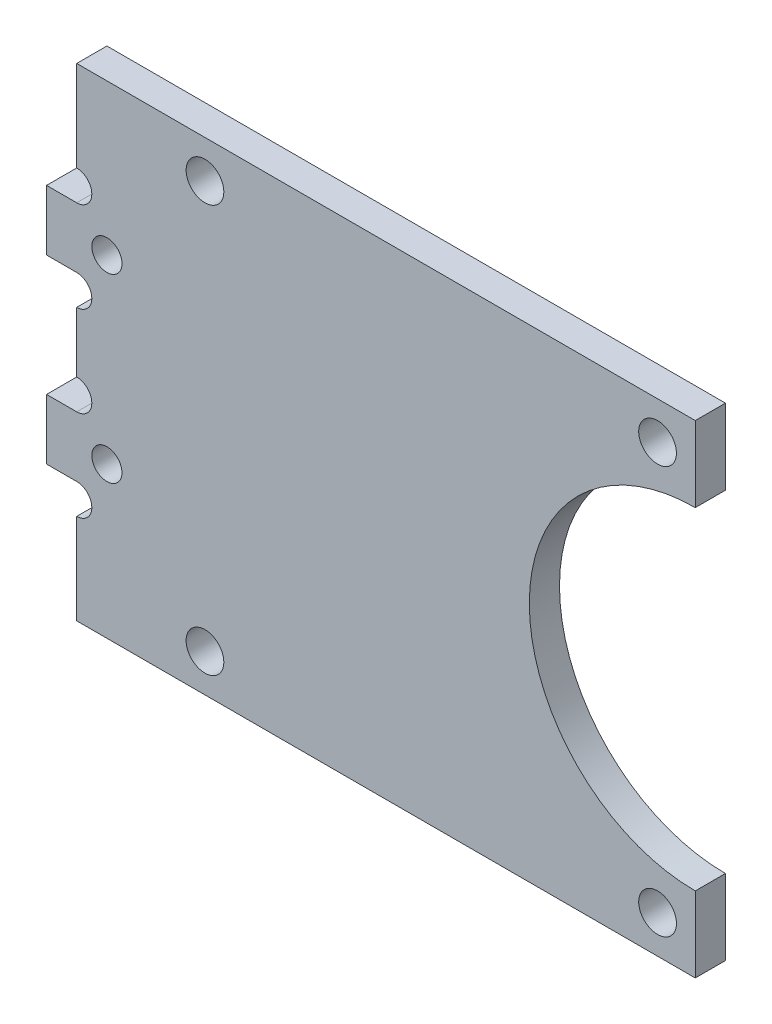
SolidWorks part; units mm, degrees
material "自訂玻璃纖維"
ref_plane "前基準面" through (0, 0, 0) normal (0, 0, 1) x (1, 0, 0)
ref_plane "上基準面" through (0, 0, 0) normal (0, 1, 0) x (1, 0, 0)
ref_plane "右基準面" through (0, 0, 0) normal (1, 0, 0) x (0, 0, -1)
sketch "草圖1" plane through (0, 0, 0) normal (0, 0, 1) x (1, 0, 0)
  line L0 (-17.2162, 10.1625) -> (15.2838, 10.1625)
  line L1 (15.2838, 10.1625) -> (15.2838, -21.8375)
  line L2 (15.2838, -21.8375) -> (-17.2162, -21.8375)
  line L3 (-25.7162, -3.8375) -> (-25.7162, -7.8375)
  line L4 (-25.7162, 2.1625) -> (-27.7162, 2.1625)
  line L5 (-17.2162, 10.1625) -> (-19.7162, 10.1625)
  line L6 (-27.7162, -9.8375) -> (-27.7162, -13.8375)
  line L7 (-17.2162, -21.8375) -> (-19.7162, -21.8375)
  line L8 (-25.7162, -1.8375) -> (-27.7162, -1.8375)
  line L9 (-19.7162, 10.1625) -> (-25.7162, 10.1625)
  line L10 (-27.7162, 2.1625) -> (-27.7162, -1.8375)
  line L11 (-19.7162, -21.8375) -> (-25.7162, -21.8375)
  line L12 (-25.7162, 10.1625) -> (-25.7162, 4.1625)
  line L13 (-25.7162, -9.8375) -> (-27.7162, -9.8375)
  line L14 (-25.7162, -13.8375) -> (-27.7162, -13.8375)
  line L15 (-25.7162, -15.8375) -> (-25.7162, -21.8375)
  circle A0 centre (-17.2162, 7.6625) radius 1.25
  circle A1 centre (-17.2162, -19.3375) radius 1.25
  circle A2 centre (12.7838, -19.3375) radius 1.25
  circle A3 centre (12.7838, 7.6625) radius 1.25
  arc A4 (-25.7162, 2.1625) -> (-25.7162, 4.1625) centre (-25.7162, 3.1625) ccw
  circle A5 centre (-23.7162, 0.1625) radius 1
  circle A6 centre (-23.7162, -11.8375) radius 1
  arc A7 (-25.7162, -1.8375) -> (-25.7162, -3.8375) centre (-25.7162, -2.8375) cw
  arc A8 (-25.7162, -13.8375) -> (-25.7162, -15.8375) centre (-25.7162, -14.8375) cw
  arc A9 (-25.7162, -9.8375) -> (-25.7162, -7.8375) centre (-25.7162, -8.8375) ccw
  dimension "D7" = 2
  dimension "D8" = 4
  dimension "D9" = 2
  dimension "D10" = 2
  dimension "D12" = 4
  dimension "D13" = 12
  dimension "D4" = 2.5
  dimension "D5" = 30
  dimension "D6" = 2
  dimension "D2" = 2.5
  dimension "D3" = 35
  dimension "D11" = 6
extrude "填料-伸長1" add sketch "草圖1" along normal blind 2
sketch "草圖4" plane through (0, 0, 0) normal (0, 0, -1) x (-1, 0, 0)
  line L1 (-15.2838, -21.8375) -> (-15.2838, 10.1625) construction
  line L4 (-15.2838, -16.8375) -> (-15.2838, 5.1625)
  arc A2 (-15.2838, 5.1625) -> (-15.2838, -16.8375) centre (-15.2838, -5.8375) cw
extrude "除料-伸長4" cut sketch "草圖4" against normal blind 10
